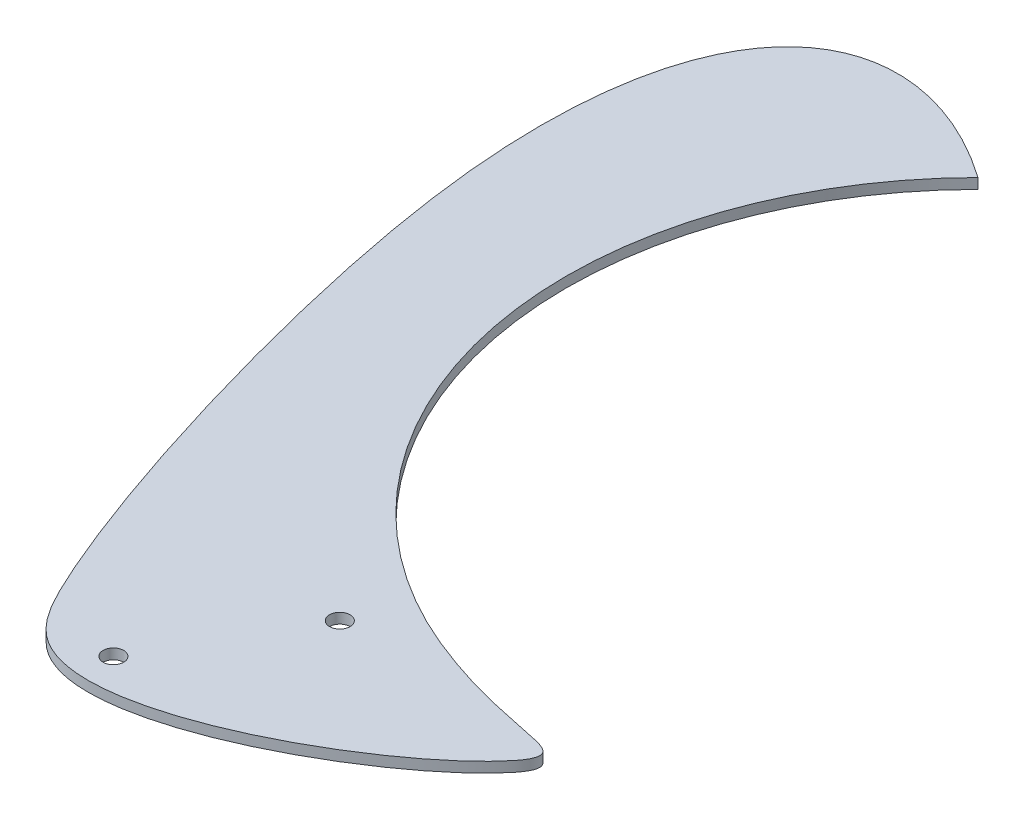
SolidWorks part; units mm, degrees
ref_plane "Front" through (0, 0, 0) normal (0, 0, 1) x (1, 0, 0)
ref_plane "Top" through (0, 0, 0) normal (0, 1, 0) x (1, 0, 0)
ref_plane "Right" through (0, 0, 0) normal (1, 0, 0) x (0, 0, -1)
sketch "Sketch1" plane through (0, 0, 0) normal (0, 1, 0) x (1, 0, 0)
  line L0 (0, 0) -> (0, -366.2696) construction
  line L1 (-179.6051, -179.6051) -> (179.6051, -179.6051) construction
  line L2 (-179.6051, -179.6051) -> (-179.6051, 179.6051) construction
  line L3 (-179.6051, 179.6051) -> (179.6051, 179.6051) construction
  line L4 (179.6051, -179.6051) -> (179.6051, 179.6051) construction
  line L5 (-179.6051, -179.6051) -> (179.6051, 179.6051) construction
  line L6 (-179.6051, 179.6051) -> (179.6051, -179.6051) construction
  line L7 (-97.2016, 234.6654) -> (97.2016, 234.6654) construction
  line L8 (-97.2016, 234.6654) -> (-97.2016, -234.6654) construction
  line L9 (-97.2016, -234.6654) -> (97.2016, -234.6654) construction
  line L10 (97.2016, 234.6654) -> (97.2016, -234.6654) construction
  line L11 (-97.2016, 234.6654) -> (97.2016, -234.6654) construction
  line L12 (-97.2016, -234.6654) -> (97.2016, 234.6654) construction
  arc A0 (-179.6051, 179.6051) -> (-97.2016, -234.6654) centre (0, 0) ccw
  circle A1 centre (0, 0) radius 254 construction
  circle A2 centre (-139.7, -254.0585) radius 6.35
  circle A3 centre (-190.5, -342.9585) radius 6.35
  spline S0 degree 3 poles (-179.6051, 179.6051) (-280.5737, 250.5482) (-407.98, 177.8907) (-268.8239, -278.2705) (-199.5455, -402.8677) (-35.2574, -312.8132) (4.0323, -253.3533) (-44.0747, -256.5196) (-97.2016, -234.6654) knots 0 0 0 0 0.421503 0.634965 0.685832 0.903025 0.937157 1 1 1 1
  point P18 (0, 0)
  point P19 (-14.1343, -292.0828)
  point P20 (-5.9499, -264.0978)
  dimension "D1" = 508
  dimension "D4" = 139.7
  dimension "D2" = 90
  dimension "D3" = 45
  dimension "D5" = 190.5
  dimension "D6" = 88.9
extrude "Boss-Extrude1" add sketch "Sketch1" along normal blind 6.35
